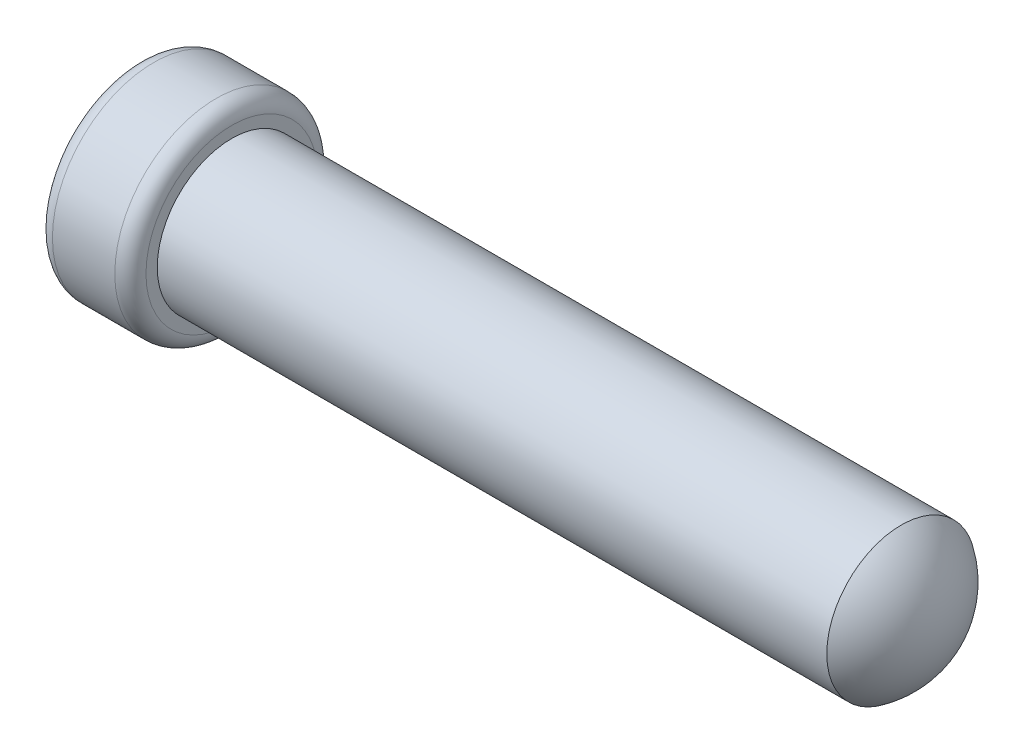
SolidWorks part; units mm, degrees
material "Brass Alloy 385"
ref_plane "Front Plane" through (0, 0, 0) normal (0, 0, 1) x (1, 0, 0)
ref_plane "Top Plane" through (0, 0, 0) normal (0, 1, 0) x (1, 0, 0)
ref_plane "Right Plane" through (0, 0, 0) normal (1, 0, 0) x (0, 0, -1)
sketch "Sketch1" plane through (0, 0, 0) normal (0, 0, 1) x (1, 0, 0)
  line L0 (-0.3435, 0) -> (3.097, 0) construction
  line L1 (0, 0) -> (2.6162, 0)
  line L2 (0.3048, 0.2426) -> (2.4865, 0.2426)
  line L3 (0.3048, 0.2426) -> (0.3048, 0.2794)
  line L4 (0.0508, 0.3302) -> (0.254, 0.3302)
  line L6 (0, 0) -> (0, 0.2794)
  arc A0 (0.3048, 0.2794) -> (0.254, 0.3302) centre (0.254, 0.2794) ccw
  arc A1 (0, 0.2794) -> (0.0508, 0.3302) centre (0.0508, 0.2794) cw
  arc A2 (2.6162, 0) -> (2.4865, 0.2426) centre (2.3221, -0.0013) ccw
revolve "RevolutionAngle1" add sketch "Sketch1" angle 360 about L0
